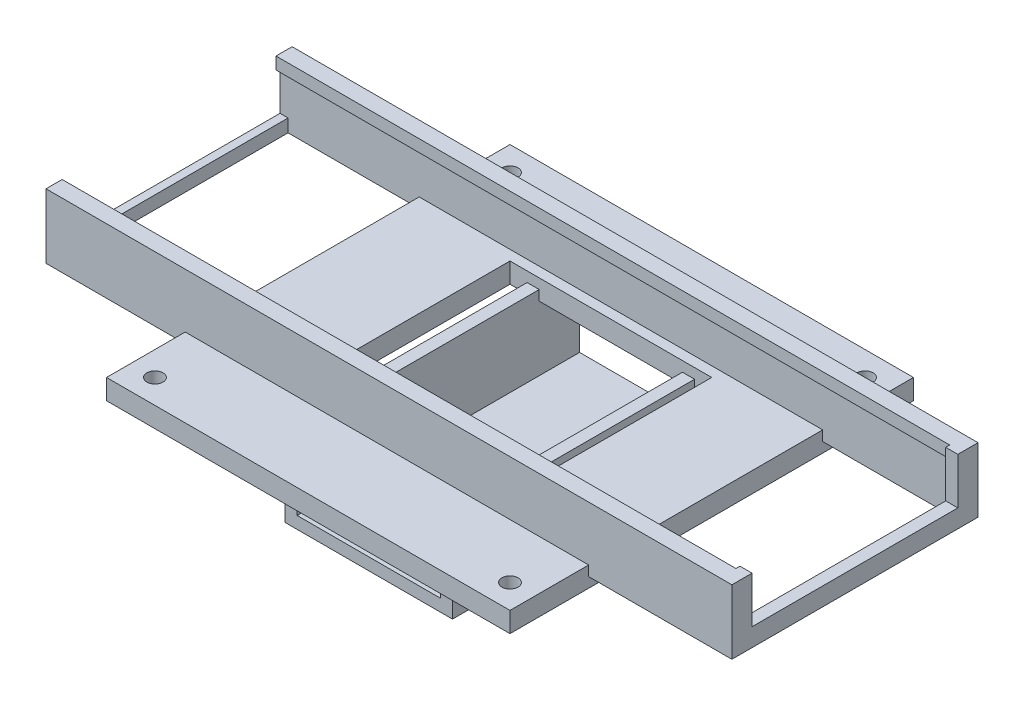
SolidWorks part; units mm, degrees
ref_plane "정면" through (0, 0, 0) normal (0, 0, 1) x (1, 0, 0)
ref_plane "윗면" through (0, 0, 0) normal (0, 1, 0) x (1, 0, 0)
ref_plane "우측면" through (0, 0, 0) normal (1, 0, 0) x (0, 0, -1)
sketch "스케치2" plane through (0, 0, 0) normal (0, 1, 0) x (1, 0, 0)
  line L1 (50, 50) -> (-50, 50)
  line L2 (50, 50) -> (50, -50)
  line L3 (50, -50) -> (-50, -50)
  line L4 (-50, 50) -> (-50, -50)
  line L5 (50, 50) -> (-50, -50) construction
  line L6 (50, -50) -> (-50, 50) construction
  line L7 (-25, 25) -> (25, 25)
  line L8 (-25, 25) -> (-25, -25)
  line L9 (-25, -25) -> (25, -25)
  line L10 (25, 25) -> (25, -25)
  line L11 (-25, 25) -> (25, -25) construction
  line L12 (-25, -25) -> (25, 25) construction
  circle A0 centre (-44, 44) radius 2
  circle A1 centre (44, 44) radius 2
  circle A2 centre (-44, -44) radius 2
  circle A3 centre (44, -44) radius 2
  point P0 (0, 0)
  point P6 (0, 0)
  dimension "D5" = 4
  dimension "D1" = 100
  dimension "D2" = 100
  dimension "D3" = 50
  dimension "D4" = 50
  dimension "D6" = 6
  dimension "D7" = 6
  dimension "D8" = 6
  dimension "D9" = 6
extrude "보스-돌출1" add sketch "스케치2" along normal mid plane 5
sketch "스케치3" plane through (0, 0, 0) normal (1, 0, 0) x (0, 0, -1)
  line L0 (0, 0) -> (65.789, 0) construction
  line L1 (0, 0) -> (0, -30.3674) construction
  line L2 (-30.5, 0) -> (-30.5, 16)
  line L3 (-30.5, 16) -> (-26.5, 16)
  line L4 (-26.5, 16) -> (-26.5, 13)
  line L5 (-26.5, 13) -> (-27.5, 13)
  line L6 (-27.5, 13) -> (-27.5, 0)
  line L7 (-27.5, 0) -> (-30.5, 0)
  line L14 (-50, 2.5) -> (50, 2.5) construction
  line L15 (27.5, 0) -> (30.5, 0)
  line L16 (27.5, 13) -> (27.5, 0)
  line L17 (26.5, 13) -> (27.5, 13)
  line L18 (26.5, 16) -> (26.5, 13)
  line L19 (30.5, 16) -> (26.5, 16)
  line L20 (30.5, 0) -> (30.5, 16)
  dimension "D1" = 27.5
  dimension "D2" = 3
  dimension "D3" = 10.5
  dimension "D4" = 3
  dimension "D5" = 1
extrude "보스-돌출2" add sketch "스케치3" along normal mid plane 165
sketch "스케치4" plane through (82.5, 0, 0) normal (1, 0, 0) x (0, 0, -1)
  line L7 (-30.5, 16) -> (-25.5, 16)
  line L14 (25.5, 16) -> (30.5, 16)
  line L15 (30.5, 16) -> (30.5, 0)
  line L16 (30.5, 0) -> (-30.5, 0)
  line L17 (-30.5, 0) -> (-30.5, 16)
  line L18 (-25.5, 16) -> (-25.5, 4.5)
  line L19 (-25.5, 4.5) -> (25.5, 4.5)
  line L20 (25.5, 4.5) -> (25.5, 16)
  line L21 (-27.5, 2.5) -> (27.5, 2.5) construction
  line L22 (-27.5, 0) -> (-27.5, 13) construction
  line L23 (27.5, 13) -> (27.5, 0) construction
  dimension "D1" = 2
  dimension "D2" = 2
  dimension "D3" = 2
extrude "보스-돌출3" add sketch "스케치4" along normal blind 3
sketch "스케치6" plane through (0, 0, 0) normal (0, 0, 1) x (1, 0, 0)
  line L0 (0, 0) -> (50000, 0) construction
  line L2 (0, 0) -> (0, -50000) construction
  line L3 (-20.75, 0) -> (-20.75, -21.5)
  line L4 (-20.75, -21.5) -> (20.75, -21.5)
  line L6 (17.75, -18.5) -> (-17.75, -18.5)
  line L7 (-17.75, -18.5) -> (-17.75, 0)
  line L8 (-17.75, 0) -> (-20.75, 0)
  line L9 (17.75, 0) -> (20.75, 0)
  line L10 (17.75, -18.5) -> (17.75, 0)
  line L11 (20.75, 0) -> (20.75, -21.5)
  line L12 (-50, -2.5) -> (50, -2.5) construction
  point P14 (0, -18.5)
  point P15 (0, -21.5)
  dimension "D1" = 35.5
  dimension "D2" = 3
  dimension "D3" = 16
  dimension "D4" = 3
extrude "보스-돌출4" add sketch "스케치6" along normal mid plane 70
sketch "스케치7" plane through (-82.5, 0, 0) normal (-1, 0, 0) x (0, 0, 1)
  line L3 (27.5, 3.2) -> (-27.5, 3.2)
  line L4 (30.5, 16) -> (26.5, 16)
  line L5 (30.5, 0) -> (30.5, 16)
  line L6 (-26.5, 16) -> (-30.5, 16)
  line L7 (-30.5, 16) -> (-30.5, 0)
  line L8 (-30.5, 0) -> (30.5, 0)
  line L9 (-26.5, 16) -> (-26.5, 13)
  line L10 (-26.5, 13) -> (-27.5, 13) construction
  line L11 (-26.5, 13) -> (-27.5, 13) construction
  line L12 (-26.5, 13) -> (-27.5, 13)
  line L13 (-27.5, 13) -> (-27.5, 3.2)
  line L14 (-27.5, 13) -> (-27.5, 0) construction
  line L15 (26.5, 16) -> (26.5, 13)
  line L16 (26.5, 13) -> (27.5, 13)
  line L17 (27.5, 13) -> (27.5, 3.2)
  line L18 (27.5, 0) -> (27.5, 13) construction
  line L19 (-27.5, 2.5) -> (27.5, 2.5) construction
  point P31 (0, 0)
  dimension "D1" = 0.7
extrude "보스-돌출5" add sketch "스케치7" along normal blind 2
